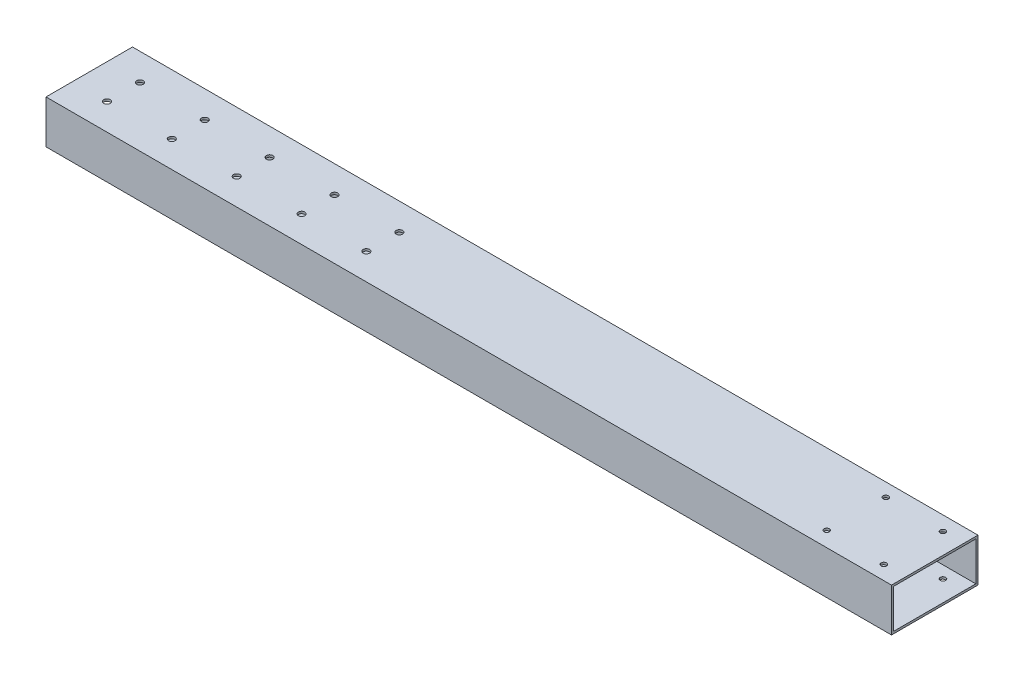
SolidWorks part; units mm, degrees
ref_plane "前视基准面" through (0, 0, 0) normal (0, 0, 1) x (1, 0, 0)
ref_plane "上视基准面" through (0, 0, 0) normal (0, 1, 0) x (1, 0, 0)
ref_plane "右视基准面" through (0, 0, 0) normal (1, 0, 0) x (0, 0, -1)
sketch "草图1" plane through (0, 0, 0) normal (1, 0, 0) x (0, 0, -1)
  line L1 (-20, -10) -> (20, -10)
  line L2 (-20, -10) -> (-20, 10)
  line L3 (-20, 10) -> (20, 10)
  line L4 (20, -10) -> (20, 10)
  line L5 (-20, -10) -> (20, 10) construction
  line L6 (-20, 10) -> (20, -10) construction
  point P0 (0, 0)
  dimension "D1" = 40
  dimension "D2" = 20
extrude "凸台-拉伸1" add sketch "草图1" along normal blind 391
shell "抽壳1" thickness 1
sketch "草图2" plane through (0, 10, 0) normal (0, 1, 0) x (1, 0, 0)
  circle A0 centre (15.9211, 7.4954) radius 1.5 construction
  circle A1 centre (45.9211, 7.4954) radius 1.5 construction
  circle A2 centre (75.9211, 7.4954) radius 1.5 construction
  circle A3 centre (105.9211, 7.4954) radius 1.5 construction
  circle A4 centre (135.9211, 7.4954) radius 1.5 construction
  circle A5 centre (15.9211, -7.7358) radius 1.5 construction
  circle A6 centre (45.9211, -7.7358) radius 1.5 construction
  circle A7 centre (75.9211, -7.7358) radius 1.5 construction
  circle A8 centre (105.9211, -7.7358) radius 1.5 construction
  circle A9 centre (135.9211, -7.7358) radius 1.5 construction
  circle A10 centre (15.9211, 7.4954) radius 1.5
  circle A11 centre (45.9211, 7.4954) radius 1.5
  circle A12 centre (75.9211, 7.4954) radius 1.5
  circle A13 centre (105.9211, 7.4954) radius 1.5
  circle A14 centre (135.9211, 7.4954) radius 1.5
  circle A15 centre (15.9211, -7.7358) radius 1.5
  circle A16 centre (45.9211, -7.7358) radius 1.5
  circle A17 centre (75.9211, -7.7358) radius 1.5
  circle A18 centre (105.9211, -7.7358) radius 1.5
  circle A19 centre (135.9211, -7.7358) radius 1.5
extrude "切除-拉伸1" cut sketch "草图2" against normal blind 48
sketch "草图3" plane through (0, -10, 0) normal (0, -1, 0) x (1, 0, 0)
  circle A0 centre (354.561, -13.8354) radius 1.25 construction
  circle A1 centre (381.4269, -13.3612) radius 1.25 construction
  circle A2 centre (380.9527, 13.5047) radius 1.25 construction
  circle A3 centre (354.0868, 13.0305) radius 1.25 construction
  circle A4 centre (354.561, -13.8354) radius 1.25
  circle A5 centre (381.4269, -13.3612) radius 1.25
  circle A6 centre (380.9527, 13.5047) radius 1.25
  circle A7 centre (354.0868, 13.0305) radius 1.25
extrude "切除-拉伸2" cut sketch "草图3" against normal blind 37
